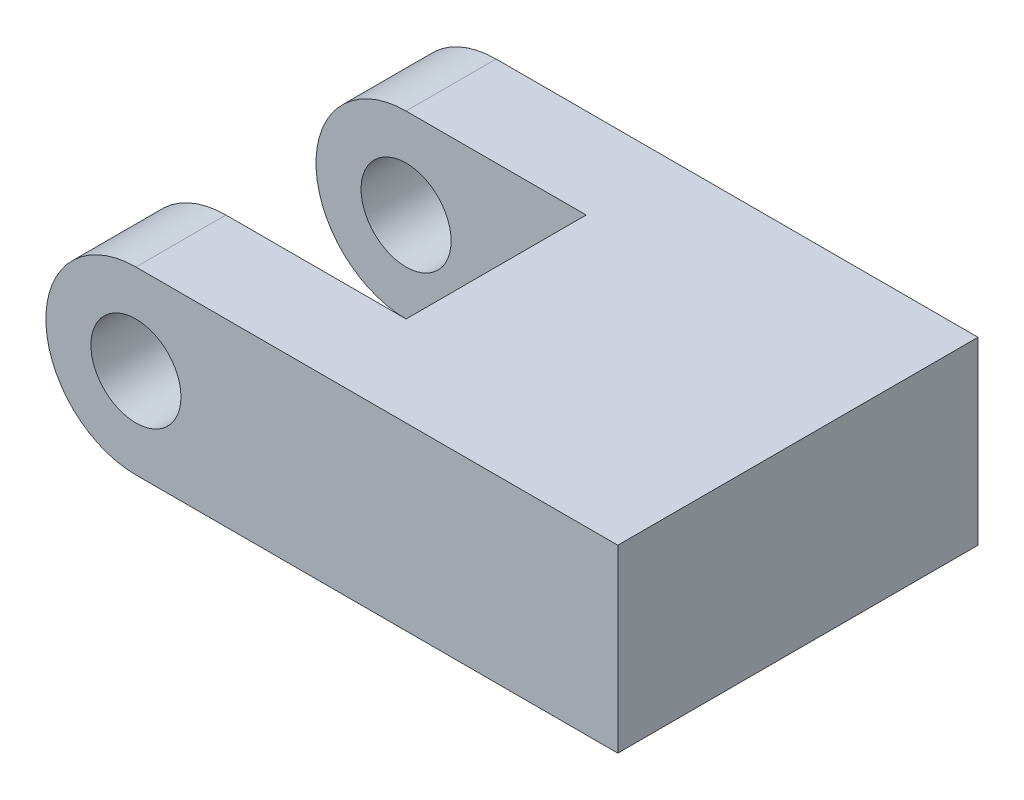
SolidWorks part; units mm, degrees
ref_plane "Front Plane" through (0, 0, 0) normal (0, 0, 1) x (1, 0, 0)
ref_plane "Top Plane" through (0, 0, 0) normal (0, 1, 0) x (1, 0, 0)
ref_plane "Right Plane" through (0, 0, 0) normal (1, 0, 0) x (0, 0, -1)
sketch "Sketch1" plane through (0, 0, 0) normal (0, 0, 1) x (1, 0, 0)
  line L0 (0, 10) -> (53.5123, 10)
  line L1 (53.5123, 10) -> (53.5123, -10)
  line L2 (53.5123, -10) -> (0, -10)
  circle A0 centre (0, 0) radius 10
  dimension "D1" = 20
extrude "Boss-Extrude1" add sketch "Sketch1" along normal blind 40 contours A0 | A0 L2 L1 L0
ref_plane "Plane1" through (0, 0, 0) normal (1, 0, 0) x (0, 0, -1)
sketch "Sketch2" plane through (0, 0, 0) normal (1, 0, 0) x (0, 0, -1)
  line L0 (0, 0) -> (-40, 0) construction
  line L1 (-40, 10) -> (-40, -10) construction
  line L3 (-10, 14.4724) -> (-30, 14.4724)
  line L4 (-10, 14.4724) -> (-10, -14.4724)
  line L5 (-10, -14.4724) -> (-30, -14.4724)
  line L6 (-30, 14.4724) -> (-30, -14.4724)
  line L7 (-10, 14.4724) -> (-30, -14.4724) construction
  line L8 (-10, -14.4724) -> (-30, 14.4724) construction
  point P5 (-20, 0)
  dimension "D1" = 20
extrude "Cut-Extrude1" cut sketch "Sketch2" against normal blind 40 and the other way blind 20
sketch "Sketch3" plane through (0, 0, 40) normal (0, 0, 1) x (1, 0, 0)
  circle A0 centre (0, 0) radius 5
  dimension "D1" = 10
extrude "Cut-Extrude3" cut sketch "Sketch3" against normal blind 40
ref_plane "Plane2" through (0, 0, 30) normal (0, 0, 1) x (1, 0, 0)
